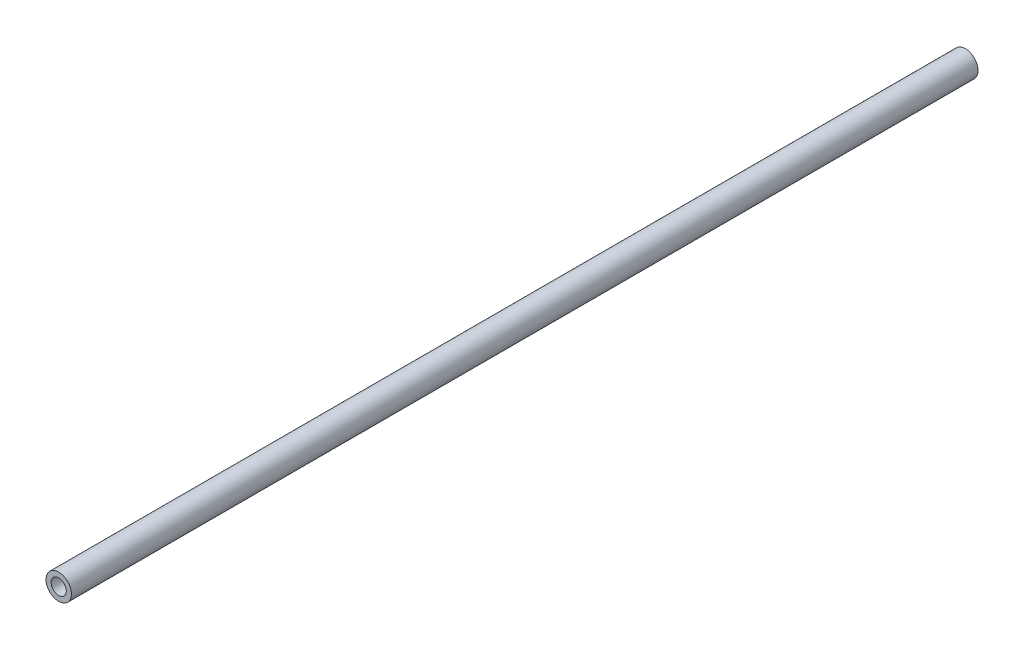
SolidWorks part; units mm, degrees
ref_plane "Front Plane" through (0, 0, 0) normal (0, 0, 1) x (1, 0, 0)
ref_plane "Top Plane" through (0, 0, 0) normal (0, 1, 0) x (1, 0, 0)
ref_plane "Right Plane" through (0, 0, 0) normal (1, 0, 0) x (0, 0, -1)
sketch "Sketch1" plane through (0, 0, 0) normal (0, 0, 1) x (1, 0, 0)
  line L0 (-8.5328, 0) -> (-5.1181, 0) construction
  line L1 (-5.1181, 0) -> (5.1181, 0) construction
  line L2 (5.1181, 0) -> (8.5328, 0) construction
  line L3 (0, 0) -> (-4.2664, -7.3896) construction
  circle A0 centre (0, 0) radius 8.5328
  circle A1 centre (0, 0) radius 5.1181
  point P8 (-4.2664, -7.3896)
  dimension "OD" = 17.0656
  dimension "ID" = 10.2362
  dimension "Wall Thickness" = 3.4147
  dimension "D1" = 60
sketch "Sketch2" plane through (0, 0, 0) normal (1, 0, 0) x (0, 0, -1)
  line L0 (-304.8, 0) -> (304.8, 0) construction
  point P2 (-283.468, 0)
  point P3 (283.468, 0)
  dimension "Length" = 609.6
  dimension "D1" = 21.332
  dimension "D2" = 21.332
sketch "Sketch3" plane through (0, 0, 0) normal (0, 0, 1) x (1, 0, 0)
  circle A0 centre (0, 0) radius 8.5328 construction
  circle A1 centre (0, 0) radius 5.1181 construction
  circle A2 centre (0, 0) radius 8.5328
  circle A3 centre (0, 0) radius 5.1181
extrude "Boss-Extrude1" add sketch "Sketch3" along normal up to vertex (304.8 mm away) and the other way up to vertex (304.8 mm away) up to point (0, 0, 304.8) other way up to point (0, 0, -304.8)
equation "\"D1@Sketch2\"=\"OD@Sketch1\"*1.25"
equation "\"D2@Sketch2\"=\"OD@Sketch1\"*1.25"
